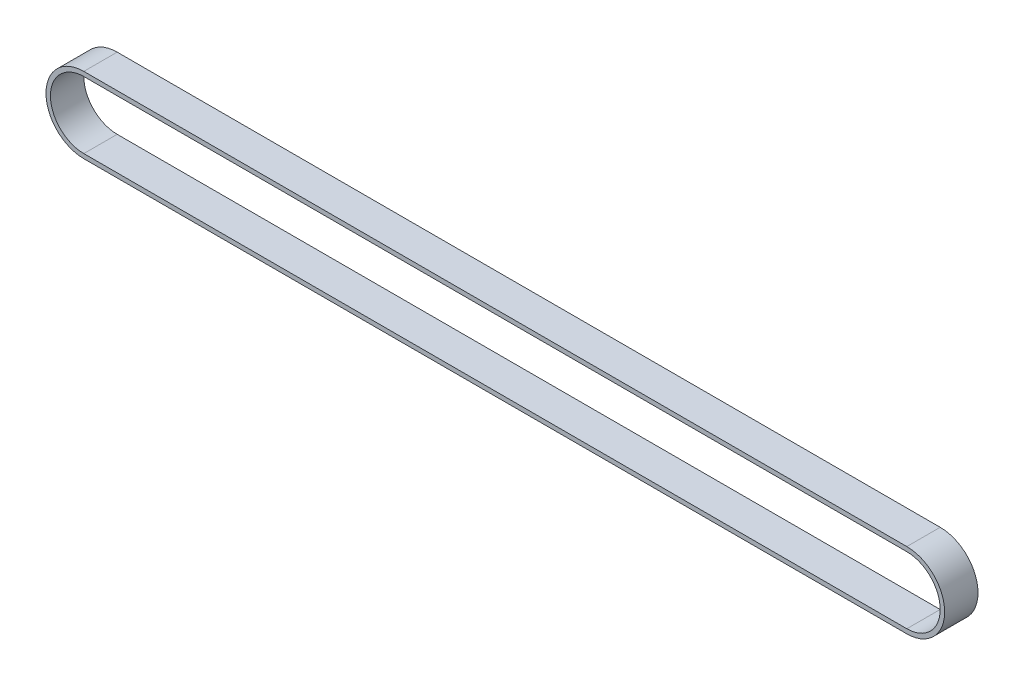
SolidWorks part; units mm, degrees
ref_plane "정면" through (0, 0, 0) normal (0, 0, 1) x (1, 0, 0)
ref_plane "윗면" through (0, 0, 0) normal (0, 1, 0) x (1, 0, 0)
ref_plane "우측면" through (0, 0, 0) normal (1, 0, 0) x (0, 0, -1)
sketch "스케치1" plane through (0, 0, 0) normal (0, 0, 1) x (1, 0, 0)
  line L0 (0, 0) -> (370, 0) construction
  line L1 (0, 15) -> (370, 15)
  line L3 (0, 17) -> (370, 17)
  line L4 (0, -17) -> (370, -17)
  line L7 (370, -15) -> (0, -15)
  circle A0 centre (0, 0) radius 15
  circle A1 centre (370, 0) radius 15
  circle A2 centre (0, 0) radius 5
  circle A3 centre (370, 0) radius 5
  circle A4 centre (0, 0) radius 17
  circle A5 centre (370, 0) radius 17
  point P21 (0, 0)
  point P22 (0, 0)
  point P23 (0, 0)
  dimension "D1" = 30
  dimension "D2" = 30
  dimension "D3" = 370
  dimension "D4" = 10
  dimension "D5" = 2
  dimension "D6" = 2
extrude "보스-돌출3" add sketch "스케치1" along normal blind 15 contours L1 A4 L7 A0 | A5 L3 A4 L1 | A5 L7 A4 L4 | A5 L1 A1 L7
